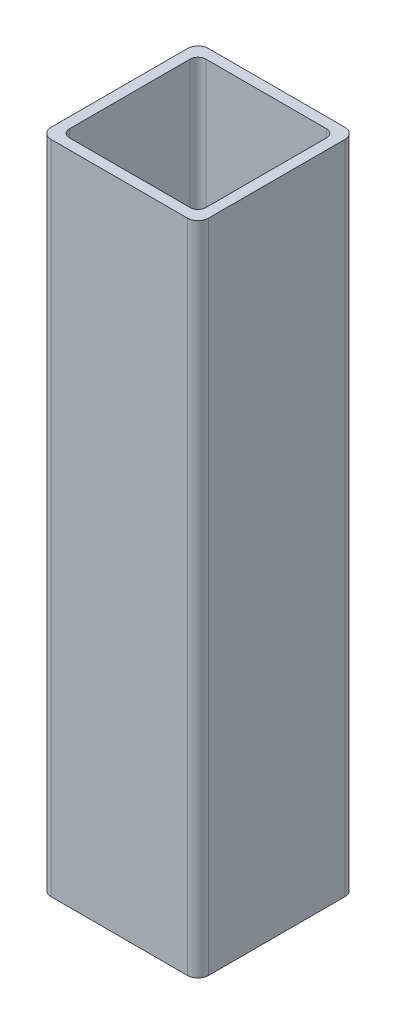
SolidWorks part; units mm, degrees
material "AISI 1020"
ref_plane "Спереди" through (0, 0, 0) normal (0, 0, 1) x (1, 0, 0)
ref_plane "Сверху" through (0, 0, 0) normal (0, 1, 0) x (1, 0, 0)
ref_plane "Справа" through (0, 0, 0) normal (1, 0, 0) x (0, 0, -1)
sketch "Эскиз1" plane through (0, 0, 0) normal (0, 1, 0) x (1, 0, 0)
  line L0 (1005, 0) -> (0, 0) construction
  line L1 (0, 1080) -> (0, 0) construction
  line B0 (-56, 0) -> (-4, 0)
  line B1 (-60, -4) -> (-60, -56)
  line B2 (-56, -60) -> (-4, -60)
  line B3 (0, -4) -> (0, -56)
  line B4 (-53, -4) -> (-7, -4)
  line B5 (-56, -7) -> (-56, -53)
  line B6 (-53, -56) -> (-7, -56)
  line B7 (-4, -7) -> (-4, -53)
  arc B8 (-60, -56) -> (-56, -60) centre (-56, -56) ccw
  arc B9 (-4, -60) -> (0, -56) centre (-4, -56) ccw
  arc B10 (-4, 0) -> (0, -4) centre (-4, -4) cw
  arc B11 (-56, 0) -> (-60, -4) centre (-56, -4) ccw
  arc B12 (-56, -53) -> (-53, -56) centre (-53, -53) ccw
  arc B13 (-7, -56) -> (-4, -53) centre (-7, -53) ccw
  arc B14 (-7, -4) -> (-4, -7) centre (-7, -7) cw
  arc B15 (-53, -4) -> (-56, -7) centre (-53, -7) ccw
sketch_block_instance "60х60х4-1"
sketch_block "60х60х4" parameters "D3"=4, "D4"=3, "D1"=60, "D2"=4
extrude "Бобышка-Вытянуть1" add sketch "Эскиз1" along normal blind 100 and the other way blind 150
